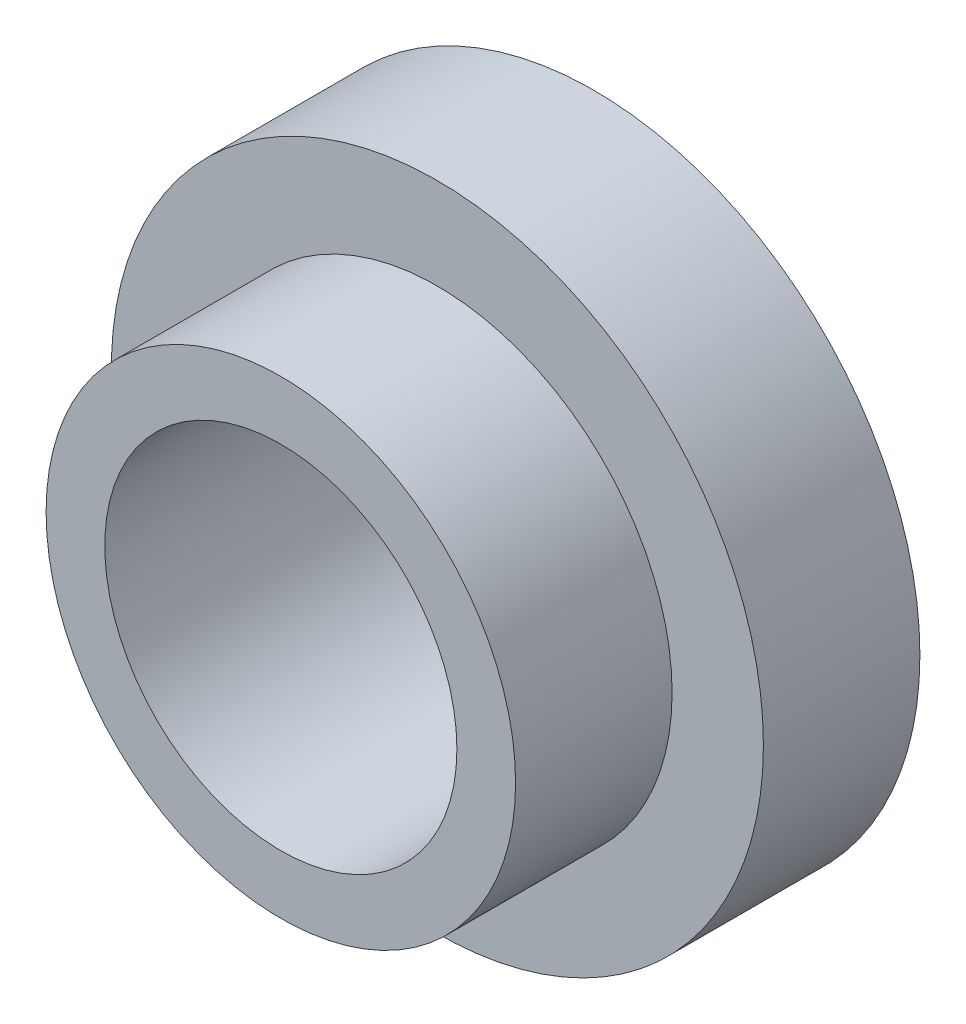
SolidWorks part; units mm, degrees
ref_plane "Płaszczyzna przednia" through (0, 0, 0) normal (0, 0, 1) x (1, 0, 0)
ref_plane "Płaszczyzna górna" through (0, 0, 0) normal (0, 1, 0) x (1, 0, 0)
ref_plane "Płaszczyzna prawa" through (0, 0, 0) normal (1, 0, 0) x (0, 0, -1)
sketch "Sketch1" plane through (0, 0, 0) normal (0, 0, 1) x (1, 0, 0)
  circle A0 centre (0, 0) radius 25
  circle A1 centre (0, 0) radius 5.5
  circle A2 centre (0, 11) radius 1.55
  circle A3 centre (0, 0) radius 11 construction
  circle A4 centre (9.5263, 5.5) radius 1.55
  circle A5 centre (9.5263, -5.5) radius 1.55
  circle A6 centre (0, -11) radius 1.55
  circle A7 centre (-9.5263, -5.5) radius 1.55
  circle A8 centre (-9.5263, 5.5) radius 1.55
  point P20 (0, 0)
  dimension "D1" = 6
  dimension "D2" = 3.1
  dimension "D3" = 11
  dimension "D4" = 22
  dimension "D5" = 50
extrude "Boss-Extrude1" add sketch "Sketch1" along normal blind 4
sketch "Sketch2" plane through (0, 0, 0) normal (0, 0, -1) x (-1, 0, 0)
  circle A0 centre (0, 11) radius 2.8
  circle A1 centre (9.5263, 5.5) radius 2.8
  circle A2 centre (9.5263, -5.5) radius 2.8
  circle A3 centre (0, -11) radius 2.8
  circle A4 centre (-9.5263, -5.5) radius 2.8
  circle A5 centre (-9.5263, 5.5) radius 2.8
  point P3 (0, 0)
  point P16 (0, 0)
  dimension "D1" = 6
extrude "Cut-Extrude1" cut sketch "Sketch2" against normal blind 2.8
sketch "Sketch3" plane through (0, 0, 0) normal (0, 0, -1) x (-1, 0, 0)
  circle A0 centre (0, 18) radius 2.5
  circle A1 centre (0, 0) radius 18 construction
  circle A2 centre (18, 0) radius 2.5
  circle A3 centre (0, -18) radius 2.5
  circle A4 centre (-18, 0) radius 2.5
  point P14 (0, 0)
  dimension "D1" = 5
  dimension "D2" = 36
  dimension "D3" = 4
sketch "Sketch4" plane through (0, 0, 4) normal (0, 0, 1) x (1, 0, 0)
  circle A0 centre (0, 0) radius 18
  circle A1 centre (0, 0) radius 13.5
  dimension "D1" = 36
  dimension "D2" = 27
extrude "Boss-Extrude2" add sketch "Sketch4" along normal blind 20
sketch "Sketch5" plane through (0, 0, 4) normal (0, 0, 1) x (1, 0, 0)
  circle A0 centre (0, 0) radius 25
  circle A1 centre (0, 0) radius 18
extrude "Boss-Extrude3" add sketch "Sketch5" along normal blind 8
extrude "Cut-Extrude3" cut sketch "Sketch3" against normal blind 8
